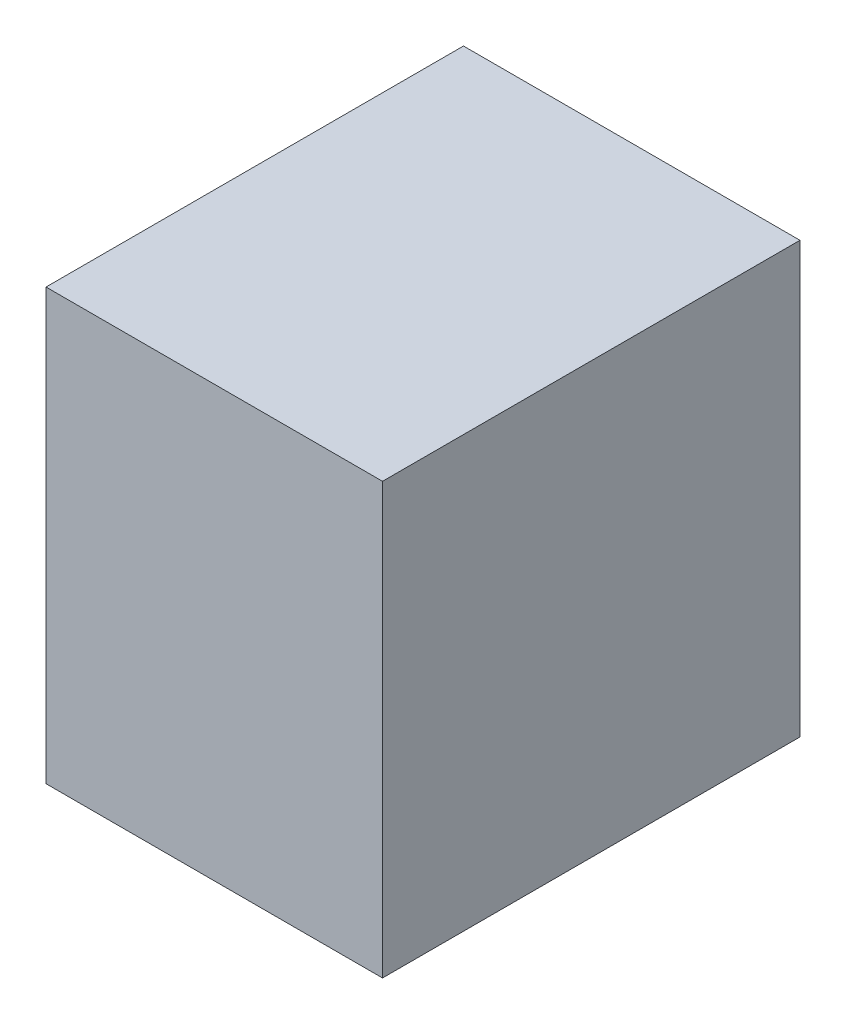
SolidWorks part; units mm, degrees
ref_plane "Front Plane" through (0, 0, 0) normal (0, 0, 1) x (1, 0, 0)
ref_plane "Top Plane" through (0, 0, 0) normal (0, 1, 0) x (1, 0, 0)
ref_plane "Right Plane" through (0, 0, 0) normal (1, 0, 0) x (0, 0, -1)
sketch "Sketch2" plane through (0, 0, 0) normal (0, 1, 0) x (1, 0, 0)
  line L0 (-39.0624, 6.1033) -> (-39.0624, -14.1587)
  line L1 (-39.0624, -14.1587) -> (-23.5024, -14.1587)
  line L2 (-23.5024, -14.1587) -> (-23.5024, 6.1033)
  line L3 (-23.5024, 6.1033) -> (-39.0624, 6.1033)
  line L4 (-41.0624, -16.1587) -> (-21.5062, -16.1587)
  line L5 (-41.0624, 8.1033) -> (-41.0624, -16.1587)
  line L6 (-41.0624, 8.1033) -> (-21.5062, 8.1033)
  line L7 (-21.5062, -16.1587) -> (-21.5062, 8.1033)
  circle A0 centre (-26.0424, 3.5633) radius 1.4855
  circle A1 centre (-26.0424, -11.6187) radius 1.5031
extrude "Boss-Extrude1" add sketch "Sketch2" along normal blind 25 contours L4 L7 L6 L5 L3 L2 L1 L0
